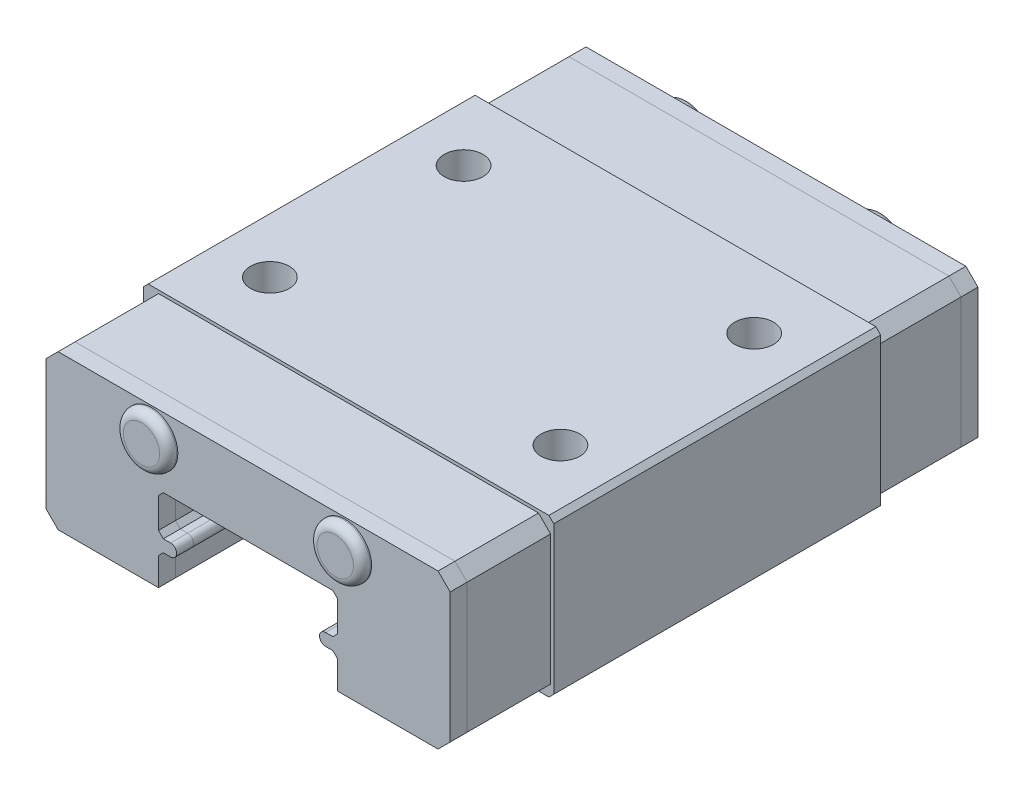
SolidWorks part; units mm, degrees
ref_plane "Front Plane" through (0, 0, 0) normal (0, 0, 1) x (1, 0, 0)
ref_plane "Top Plane" through (0, 0, 0) normal (0, 1, 0) x (1, 0, 0)
ref_plane "Right Plane" through (0, 0, 0) normal (1, 0, 0) x (0, 0, -1)
sketch "Sketch1" plane through (0, 0, 0) normal (0, 0, 1) x (1, 0, 0)
  line L0 (-8.475, 0) -> (8.475, 0)
  line L1 (8.475, 0) -> (8.475, 6.5)
  line L2 (8.475, 6.5) -> (-8.475, 6.5)
  line L3 (-8.475, 6.5) -> (-8.475, 0)
  point P4 (0, 0)
  dimension "D1" = 16.95
  dimension "D2" = 6.5
extrude "Boss-Extrude1" add sketch "Sketch1" along normal mid plane 13.5
sketch "Sketch2" plane through (0, 0, 6.75) normal (0, 0, 1) x (1, 0, 0)
  line L0 (-3.7, 0) -> (3.7, 0)
  line L1 (-8.475, 0) -> (8.475, 0) construction
  line L2 (-3.7, 0) -> (-3.7, 1.35)
  line L3 (-3.7, 3.5) -> (3.7, 3.5)
  line L4 (3.7, 3.5) -> (3.7, 1.85)
  line L5 (-3.7, 1.6) -> (-3.2, 1.6) construction
  line L6 (-3.7, 1.85) -> (-3.2, 1.85)
  line L7 (-3.7, 1.35) -> (-3.2, 1.35)
  line L8 (3.7, 1.6) -> (3.2, 1.6) construction
  line L9 (3.7, 1.35) -> (3.2, 1.35)
  line L10 (3.7, 1.85) -> (3.2, 1.85)
  line L11 (-3.7, 1.85) -> (-3.7, 3.5)
  line L12 (3.7, 1.35) -> (3.7, 0)
  arc A1 (-3.2, 1.35) -> (-3.2, 1.85) centre (-3.2, 1.6) ccw
  arc A3 (3.2, 1.85) -> (3.2, 1.35) centre (3.2, 1.6) ccw
  point P5 (0, 0)
  point P10 (0, 0)
  point P22 (-3.9, 2.0963)
  point P23 (-3.4781, 2.3878)
  point P24 (-3.4, 2.4095)
  point P25 (-5.0941, -0.0961)
  point P26 (3.4, 2.1029)
  point P28 (-3.9, 1.9947)
  point P29 (-3.9, 2.4053)
  point P30 (3.9, 2.4053)
  point P31 (3.9, 1.9947)
  dimension "D1" = 3.5
  dimension "D2" = 7.4
  dimension "D3" = 0.5
  dimension "D4" = 1.9
  dimension "D5" = 0.5
extrude "Cut-Extrude1" cut sketch "Sketch2" against normal through all both and the other way through all
chamfer "Chamfer1" distance 0.2 angle 45 10 edges at (3.7, 1.35, 0) (3.7, 1.85, 0) (-3.7, 1.35, 0) (-3.7, 1.85, 0) (3.7, 3.5, 0) (-3.7, 3.5, 0) (-8.475, 0, 0) (8.475, 0, 0) (8.475, 6.5, 0) (-8.475, 6.5, 0)
hole_wizard "Tap Drill for M2x0.4 Tap1" positions "Sketch3" profile "Sketch4" hole size "M2x0.4" standard "ANSI Metric"
sketch "Sketch3" plane through (0, 6.5, 0) normal (0, 1, 0) x (1, 0, 0)
  line L1 (6, 4) -> (-6, 4) construction
  line L2 (6, 4) -> (6, -4) construction
  line L3 (6, -4) -> (-6, -4) construction
  line L4 (-6, 4) -> (-6, -4) construction
  line L5 (6, 4) -> (-6, -4) construction
  point P0 (-6, 4)
  point P3 (6, 4)
  point P4 (-6, -4)
  point P101 (6, -4)
  point P108 (0, 0)
  dimension "D1" = 8
  dimension "D2" = 12
sketch "Sketch4" plane through (-6, 6.5, -4) normal (1, 0, 0) x (0, 0, 1)
  line L0 (0, 0) -> (0, 4.9807)
  line L1 (0, 4.9807) -> (0.8, 4.5)
  line L2 (0.8, 4.5) -> (0.8, 0)
  line L5 (0.8, 0) -> (0, 0)
  line L10 (0, 4.9807) -> (-0.8, 4.5) construction
  line L11 (0, -6.35) -> (0, 107.95) construction
  dimension "Hole Dia." = 1.6
  dimension "Hole Depth" = 4.5
  dimension "Drill Angle" = 118
sketch "Sketch5" plane through (0, 0, 6.75) normal (0, 0, 1) x (1, 0, 0)
  line L0 (-8.275, 0) -> (-3.7, 0) construction
  line L1 (-8.345, 0) -> (-3.7, 0)
  line L2 (-8.345, 0) -> (-8.345, 6.37)
  line L3 (-8.345, 6.37) -> (8.345, 6.37)
  line L4 (8.345, 0) -> (8.345, 6.37)
  line L5 (8.275, 6.5) -> (-8.275, 6.5) construction
  line L6 (-8.475, 6.3) -> (-8.475, 0.2) construction
  line L7 (8.475, 0.2) -> (8.475, 6.3) construction
  line L8 (3.7, 0) -> (3.7, 1.15) construction
  line L9 (3.5, 1.35) -> (3.2, 1.35) construction
  line L10 (3.5, 1.35) -> (3.7, 1.15) construction
  line L11 (3.2, 1.85) -> (3.5, 1.85) construction
  line L12 (3.7, 2.05) -> (3.5, 1.85) construction
  line L13 (3.7, 2.05) -> (3.7, 3.3) construction
  line L14 (3.5, 3.5) -> (3.7, 3.3) construction
  line L15 (3.5, 3.5) -> (-3.5, 3.5) construction
  line L16 (-3.7, 3.3) -> (-3.5, 3.5) construction
  line L17 (-3.7, 3.3) -> (-3.7, 2.05) construction
  line L18 (-3.5, 1.85) -> (-3.7, 2.05) construction
  line L19 (-3.5, 1.85) -> (-3.2, 1.85) construction
  line L20 (-3.2, 1.35) -> (-3.5, 1.35) construction
  line L21 (-3.7, 1.15) -> (-3.5, 1.35) construction
  line L22 (-3.7, 1.15) -> (-3.7, 0) construction
  line L23 (3.7, 0) -> (3.7, 1.15)
  line L24 (3.5, 1.35) -> (3.2, 1.35)
  line L25 (3.5, 1.35) -> (3.7, 1.15)
  line L26 (3.2, 1.85) -> (3.5, 1.85)
  line L27 (3.7, 2.05) -> (3.5, 1.85)
  line L28 (3.7, 2.05) -> (3.7, 3.3)
  line L29 (3.5, 3.5) -> (3.7, 3.3)
  line L30 (3.5, 3.5) -> (-3.5, 3.5)
  line L31 (-3.7, 3.3) -> (-3.5, 3.5)
  line L32 (-3.7, 3.3) -> (-3.7, 2.05)
  line L33 (-3.5, 1.85) -> (-3.7, 2.05)
  line L34 (-3.5, 1.85) -> (-3.2, 1.85)
  line L35 (-3.2, 1.35) -> (-3.5, 1.35)
  line L36 (-3.7, 1.15) -> (-3.5, 1.35)
  line L37 (-3.7, 1.15) -> (-3.7, 0)
  line L38 (3.7, 0) -> (8.345, 0)
  arc A0 (3.2, 1.85) -> (3.2, 1.35) centre (3.2, 1.6) ccw construction
  arc A1 (-3.2, 1.35) -> (-3.2, 1.85) centre (-3.2, 1.6) ccw construction
  arc A2 (3.2, 1.85) -> (3.2, 1.35) centre (3.2, 1.6) ccw
  arc A3 (-3.2, 1.35) -> (-3.2, 1.85) centre (-3.2, 1.6) ccw
  dimension "D1" = 0.13
  dimension "D2" = 0.13
  dimension "D3" = 0.13
extrude "Boss-Extrude2" add sketch "Sketch5" along normal blind 3.45 separate body contours L3 L4 L38 L23 L25 L24 A2 L26 L27 L28 L29 L30 L31 L32 L33 L34 A3 L35 L36 L37 L1 L2
chamfer "Chamfer2" distance 0.5 angle 45 4 edges at (-8.345, 0, 8.475) (8.345, 0, 8.475) (8.345, 6.37, 8.475) (-8.345, 6.37, 8.475)
sketch "Sketch6" plane through (0, 0, 10.2) normal (0, 0, 1) x (1, 0, 0)
  line L24 (-8.345, 5.87) -> (-8.345, 0.5)
  line L25 (-8.345, 0.5) -> (-7.845, 0)
  line L26 (-7.845, 0) -> (-3.7, 0)
  line L27 (-3.7, 0) -> (-3.7, 1.15)
  line L28 (-3.7, 1.15) -> (-3.5, 1.35)
  line L29 (-3.5, 1.35) -> (-3.2, 1.35)
  line L30 (-3.2, 1.85) -> (-3.5, 1.85)
  line L31 (-3.5, 1.85) -> (-3.7, 2.05)
  line L32 (-3.7, 2.05) -> (-3.7, 3.3)
  line L33 (-3.7, 3.3) -> (-3.5, 3.5)
  line L34 (-3.5, 3.5) -> (3.5, 3.5)
  line L35 (3.5, 3.5) -> (3.7, 3.3)
  line L36 (3.7, 3.3) -> (3.7, 2.05)
  line L37 (3.7, 2.05) -> (3.5, 1.85)
  line L38 (3.5, 1.85) -> (3.2, 1.85)
  line L39 (3.2, 1.35) -> (3.5, 1.35)
  line L40 (3.5, 1.35) -> (3.7, 1.15)
  line L41 (3.7, 1.15) -> (3.7, 0)
  line L42 (3.7, 0) -> (7.845, 0)
  line L43 (7.845, 0) -> (8.345, 0.5)
  line L44 (8.345, 0.5) -> (8.345, 5.87)
  line L45 (8.345, 5.87) -> (7.845, 6.37)
  line L46 (7.845, 6.37) -> (-7.845, 6.37)
  line L47 (-7.845, 6.37) -> (-8.345, 5.87)
  line L48 (-8.345, 5.87) -> (-8.345, 0.5)
  line L49 (-8.345, 0.5) -> (-7.845, 0)
  line L50 (-7.845, 0) -> (-3.7, 0)
  line L51 (-3.7, 0) -> (-3.7, 1.15)
  line L52 (-3.7, 1.15) -> (-3.5, 1.35)
  line L53 (-3.5, 1.35) -> (-3.2, 1.35)
  line L54 (-3.2, 1.85) -> (-3.5, 1.85)
  line L55 (-3.5, 1.85) -> (-3.7, 2.05)
  line L56 (-3.7, 2.05) -> (-3.7, 3.3)
  line L57 (-3.7, 3.3) -> (-3.5, 3.5)
  line L58 (-3.5, 3.5) -> (3.5, 3.5)
  line L59 (3.5, 3.5) -> (3.7, 3.3)
  line L60 (3.7, 3.3) -> (3.7, 2.05)
  line L61 (3.7, 2.05) -> (3.5, 1.85)
  line L62 (3.5, 1.85) -> (3.2, 1.85)
  line L63 (3.2, 1.35) -> (3.5, 1.35)
  line L64 (3.5, 1.35) -> (3.7, 1.15)
  line L65 (3.7, 1.15) -> (3.7, 0)
  line L66 (3.7, 0) -> (7.845, 0)
  line L67 (7.845, 0) -> (8.345, 0.5)
  line L68 (8.345, 0.5) -> (8.345, 5.87)
  line L69 (8.345, 5.87) -> (7.845, 6.37)
  line L70 (7.845, 6.37) -> (-7.845, 6.37)
  line L71 (-7.845, 6.37) -> (-8.345, 5.87)
  arc A2 (-3.2, 1.35) -> (-3.2, 1.85) centre (-3.2, 1.6) ccw
  arc A3 (3.2, 1.85) -> (3.2, 1.35) centre (3.2, 1.6) ccw
  arc A4 (-3.2, 1.35) -> (-3.2, 1.85) centre (-3.2, 1.6) ccw
  arc A5 (3.2, 1.85) -> (3.2, 1.35) centre (3.2, 1.6) ccw
  dimension "D1" = 0
extrude "Boss-Extrude3" add sketch "Sketch6" along normal blind 0.7 separate body
sketch "Sketch7" plane through (0, 0, 10.9) normal (0, 0, 1) x (1, 0, 0)
  line L0 (-4, 5.2) -> (4, 5.2) construction
  line L1 (0, 5.2) -> (0, 0) construction
  line L2 (8.275, 6.5) -> (-8.275, 6.5) construction
  circle A0 centre (-4, 5.2) radius 1.1
  circle A1 centre (4, 5.2) radius 1.1
  dimension "D3" = 2.2
  dimension "D1" = 8
  dimension "D2" = 1.3
extrude "Boss-Extrude4" add sketch "Sketch7" along normal blind 0.4 separate body
fillet "Fillet1" radius 0.35 1 edges at (-2.9, 5.2, 11.3)
fillet "Fillet2" radius 0.35 1 edges at (5.1, 5.2, 11.3)
mirror "Mirror1" about plane through (0, 0, 0) normal (0, 0, 1) of bodies 113 114 116 115
